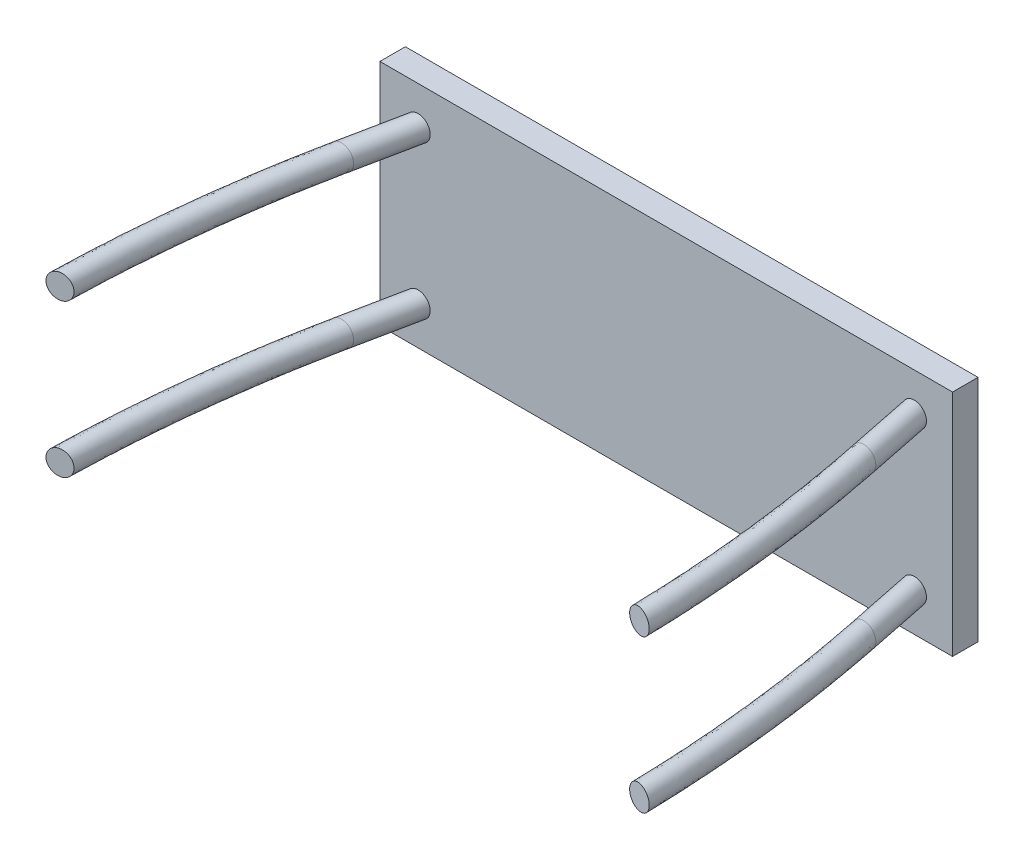
SolidWorks part; units mm, degrees
ref_plane "Front Plane" through (0, 0, 0) normal (0, 0, 1) x (1, 0, 0)
ref_plane "Top Plane" through (0, 0, 0) normal (0, 1, 0) x (1, 0, 0)
ref_plane "Right Plane" through (0, 0, 0) normal (1, 0, 0) x (0, 0, -1)
sketch "Sketch1" plane through (0, 0, 0) normal (0, 0, 1) x (1, 0, 0)
  line L5 (0, 0) -> (1143, 0)
  line L6 (0, 0) -> (0, 457.2)
  line L7 (0, 457.2) -> (1143, 457.2)
  line L8 (1143, 0) -> (1143, 457.2)
  dimension "D1" = 457.2
  dimension "D2" = 1143
extrude "TableTop" add sketch "Sketch1" along normal blind 50.8
ref_plane "Plane1" through (0, 381, 0) normal (0, 1, 0) x (1, 0, 0)
sketch "Profile" plane through (0, 0, 50.8) normal (0, 0, 1) x (1, 0, 0)
  line L0 (0, 76.2) -> (1143, 76.2) construction
  line L1 (0, 457.2) -> (0, 0) construction
  line L2 (1143, 0) -> (1143, 457.2) construction
  line L3 (0, 381) -> (1143, 381) construction
  line L4 (76.2, 457.2) -> (76.2, 0) construction
  line L5 (1143, 457.2) -> (0, 457.2) construction
  line L6 (0, 0) -> (1143, 0) construction
  line L7 (1066.8, 457.2) -> (1066.8, 0) construction
  circle A0 centre (76.2, 381) radius 24.13
  circle A1 centre (76.2, 76.2) radius 24.13 construction
  circle A2 centre (1066.8, 381) radius 24.13 construction
  circle A3 centre (1066.8, 76.2) radius 24.13 construction
  point P29 (79.9113, 76.2)
  dimension "D6" = 48.26
  dimension "D1" = 76.2
  dimension "D2" = 76.2
  dimension "D3" = 76.2
  dimension "D4" = 76.2
  dimension "D5" = 304.8
ref_point "Point1"
ref_point "Point2"
ref_point "Point3"
ref_point "Point4"
sketch "Sketch11" plane through (0, 381, 0) normal (0, 1, 0) x (1, 0, 0)
  line L0 (76.2, -50.8) -> (50.2977, -177.8)
  arc A0 (50.2977, -177.8) -> (-6.7709, -682.5843) centre (2862.3879, -751.3401) ccw
  dimension "D1" = 2869.9825
  dimension "D2" = 508
  dimension "D3" = 127
  dimension "D4" = 631.7843
sweep "Sweep1" add profiles "Profile" path "Sketch11"
ref_plane "Plane3" through (571.5, 0, 0) normal (1, 0, 0) x (0, 0, -1)
mirror "Mirror1" about plane through (571.5, 0, 0) normal (1, 0, 0) of "Sweep1"
ref_plane "Plane4" through (0, 228.6, 0) normal (0, 1, 0) x (1, 0, 0)
mirror "Mirror2" about plane through (0, 228.6, 0) normal (0, 1, 0) of "Sweep1", "Mirror1"
